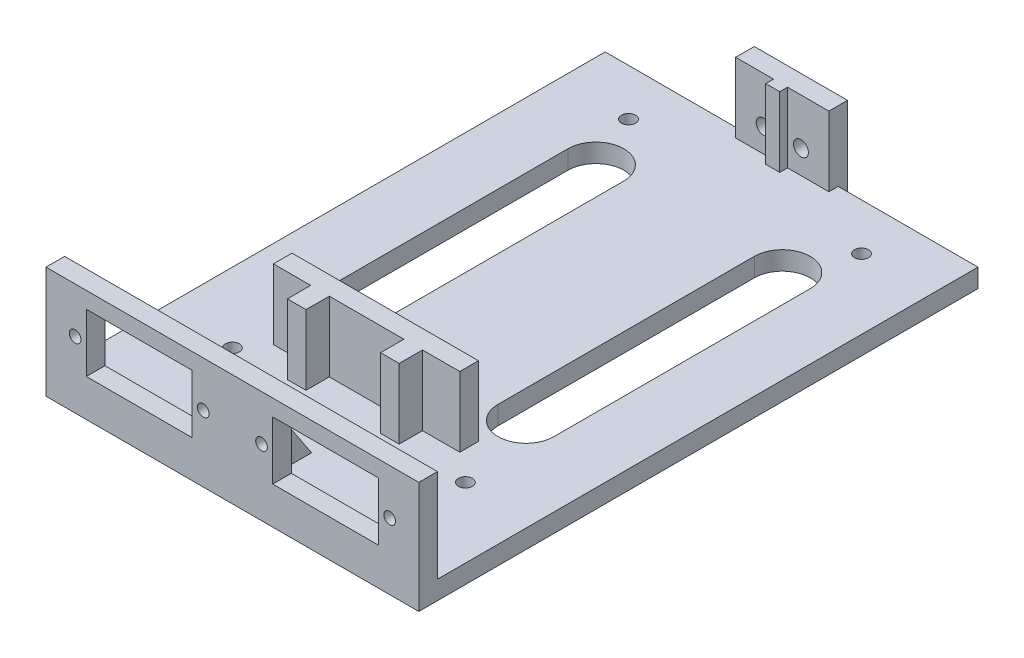
SolidWorks part; units mm, degrees
ref_plane "前视基准面" through (0, 0, 0) normal (0, 0, 1) x (1, 0, 0)
ref_plane "上视基准面" through (0, 0, 0) normal (0, 1, 0) x (1, 0, 0)
ref_plane "右视基准面" through (0, 0, 0) normal (1, 0, 0) x (0, 0, -1)
other "Configuration Table"
sketch "草图1" plane through (0, 0, 0) normal (0, 1, 0) x (1, 0, 0)
  line L0 (1.1114, 177.4615) -> (1.1114, -116.9271) construction
  line L1 (-38.8886, 30.2672) -> (41.1114, 30.2672)
  line L2 (-38.8886, 30.2672) -> (-38.8886, -89.7328)
  line L3 (-38.8886, -89.7328) -> (41.1114, -89.7328)
  line L4 (41.1114, 30.2672) -> (41.1114, -89.7328)
  circle A0 centre (-23.8886, 20.2672) radius 1.5
  circle A1 centre (26.1114, 20.2672) radius 1.5
  circle A2 centre (-23.8886, -64.7328) radius 1.5
  circle A3 centre (26.1114, -64.7328) radius 1.5
  point P4 (1.1114, -22.2328)
  point P15 (0, 0)
  point P16 (0, 61.7407)
  point P17 (0, 177.4615)
  point P26 (1.1114, 30.2672)
  dimension "D1" = 50
  dimension "D2" = 3
  dimension "D3" = 50
  dimension "D4" = 50
  dimension "D5" = 85
  dimension "D6" = 120
  dimension "D7" = 80
  dimension "D8" = 10
extrude "凸台-拉伸2" add sketch "草图1" along normal blind 4
sketch "草图4" plane through (0, 4, 0) normal (0, 1, 0) x (1, 0, 0)
  line L0 (41.1114, -89.7328) -> (41.1114, 30.2672) construction
  line L1 (-38.8886, -89.7328) -> (41.1114, -89.7328)
  line L2 (-38.8886, -89.7328) -> (-38.8886, -85.7328)
  line L3 (-38.8886, -85.7328) -> (41.1114, -85.7328)
  line L4 (41.1114, -89.7328) -> (41.1114, -85.7328)
  line L5 (-38.8886, -89.7328) -> (41.1114, -85.7328) construction
  line L6 (-38.8886, -85.7328) -> (41.1114, -89.7328) construction
  line L7 (41.1114, 30.2672) -> (-38.8886, 30.2672) construction
  line L8 (-8.8886, 32.2672) -> (11.1114, 32.2672)
  line L9 (-8.8886, 32.2672) -> (-8.8886, 28.2672)
  line L10 (-8.8886, 28.2672) -> (11.1114, 28.2672)
  line L11 (11.1114, 32.2672) -> (11.1114, 28.2672)
  line L12 (-8.8886, 32.2672) -> (11.1114, 28.2672) construction
  line L13 (-8.8886, 28.2672) -> (11.1114, 32.2672) construction
  line L14 (-38.8886, 30.2672) -> (-38.8886, -89.7328) construction
  line L15 (-23.8886, -75.7328) -> (-19.8886, -75.7328)
  line L16 (-23.8886, -75.7328) -> (-23.8886, -85.7328)
  line L17 (-23.8886, -85.7328) -> (-19.8886, -85.7328)
  line L18 (-19.8886, -75.7328) -> (-19.8886, -85.7328)
  line L19 (-23.8886, -75.7328) -> (-19.8886, -85.7328) construction
  line L20 (-23.8886, -85.7328) -> (-19.8886, -75.7328) construction
  line L21 (26.1114, -75.7328) -> (22.1114, -75.7328)
  line L22 (26.1114, -75.7328) -> (26.1114, -85.7328)
  line L23 (26.1114, -85.7328) -> (22.1114, -85.7328)
  line L24 (22.1114, -75.7328) -> (22.1114, -85.7328)
  line L25 (26.1114, -75.7328) -> (22.1114, -85.7328) construction
  line L26 (26.1114, -85.7328) -> (22.1114, -75.7328) construction
  point P4 (1.1114, -87.7328)
  point P8 (1.1114, 30.2672)
  point P19 (-21.8886, -80.7328)
  point P24 (24.1114, -80.7328)
  line M11 (-38.8886, 30.2672) -> (-38.8886, -89.7328)
  line M12 (-38.8886, -89.7328) -> (41.1114, -89.7328)
  line M13 (41.1114, -89.7328) -> (41.1114, 30.2672)
  dimension "D1" = 4
  dimension "D2" = 20
  dimension "D3" = 4
  dimension "D4" = 4
  dimension "D5" = 10
  dimension "D6" = 4
  dimension "D7" = 10
  dimension "D8" = 15
  dimension "D9" = 15
extrude "凸台-拉伸4" add sketch "草图4" along normal blind 20 contours L3 M11 M12 M13 | L21 L24 L3 L22 | L18 L15 L16 L3
sketch "草图5" plane through (0, 4, 0) normal (0, 1, 0) x (1, 0, 0)
  line L0 (41.1114, 30.2672) -> (-38.8886, 30.2672) construction
  line L1 (-8.8886, 32.2672) -> (11.1114, 32.2672)
  line L2 (-8.8886, 32.2672) -> (-8.8886, 28.2672)
  line L3 (-8.8886, 28.2672) -> (11.1114, 28.2672)
  line L4 (11.1114, 32.2672) -> (11.1114, 28.2672)
  line L5 (-8.8886, 32.2672) -> (11.1114, 28.2672) construction
  line L6 (-8.8886, 28.2672) -> (11.1114, 32.2672) construction
  point P0 (1.1114, 30.2672)
  dimension "D1" = 4
  dimension "D2" = 20
extrude "凸台-拉伸5" add sketch "草图5" along normal blind 15 and the other way blind 10
sketch "草图6" plane through (0, 0, -32.2672) normal (0, 0, -1) x (-1, 0, 0)
  line L0 (-1.1114, 20.4729) -> (-1.1114, -8.4859) construction
  circle A0 centre (2.8886, 9.0967) radius 1.6
  circle A1 centre (-5.1114, 9.0967) radius 1.6
  point P6 (0, 0)
  point P7 (0, 0)
  dimension "D1" = 8
  dimension "D2" = 3.2
  dimension "D3" = 8
extrude "切除-拉伸1" cut sketch "草图6" against normal up to next
sketch "草图9" plane through (-23.8886, 0, 0) normal (-1, 0, 0) x (0, 0, 1)
  line L0 (75.7328, 4) -> (85.7328, 14)
  line L1 (85.7328, 14) -> (85.7328, 24)
  line L2 (75.7328, 24) -> (75.7328, 4)
  line L4 (75.7328, 4) -> (85.7328, 4)
  line L5 (85.7328, 4) -> (85.7328, 24)
  line L6 (85.7328, 24) -> (75.7328, 24)
  line L7 (75.7328, 24) -> (75.7328, 4)
  line L8 (75.7328, 4) -> (85.7328, 4)
  line L9 (85.7328, 4) -> (85.7328, 24)
  line L10 (85.7328, 24) -> (75.7328, 24)
  line L11 (75.7328, 24) -> (75.7328, 4)
  dimension "D1" = 0
extrude "切除-拉伸3" cut sketch "草图9" against normal up to next contours L0 L1
sketch "草图10" plane through (0, 4, 0) normal (0, 1, 0) x (1, 0, 0)
  line L1 (-0.7696, 29.5947) -> (2.2304, 29.5947)
  line L2 (-0.7696, 29.5947) -> (-0.7696, 26.5947)
  line L3 (-0.7696, 26.5947) -> (2.2304, 26.5947)
  line L4 (2.2304, 29.5947) -> (2.2304, 26.5947)
  line L5 (-0.7696, 29.5947) -> (2.2304, 26.5947) construction
  line L6 (-0.7696, 26.5947) -> (2.2304, 29.5947) construction
  line L16 (41.1114, -85.7328) -> (41.1114, 30.2672)
  line L17 (41.1114, 30.2672) -> (11.1114, 30.2672)
  line L18 (11.1114, 30.2672) -> (11.1114, 28.2672)
  line L19 (11.1114, 28.2672) -> (-8.8886, 28.2672)
  line L20 (-8.8886, 28.2672) -> (-8.8886, 30.2672)
  line L21 (-8.8886, 30.2672) -> (-38.8886, 30.2672)
  line L22 (-38.8886, 30.2672) -> (-38.8886, -85.7328)
  line L23 (-38.8886, -85.7328) -> (-23.8886, -85.7328)
  line L24 (-23.8886, -85.7328) -> (-23.8886, -75.7328)
  line L25 (-23.8886, -75.7328) -> (-19.8886, -75.7328)
  line L26 (-19.8886, -75.7328) -> (-19.8886, -85.7328)
  line L27 (-19.8886, -85.7328) -> (22.1114, -85.7328)
  line L28 (22.1114, -85.7328) -> (22.1114, -75.7328)
  line L29 (22.1114, -75.7328) -> (26.1114, -75.7328)
  line L30 (26.1114, -75.7328) -> (26.1114, -85.7328)
  line L31 (26.1114, -85.7328) -> (41.1114, -85.7328)
  line L32 (41.1114, -85.7328) -> (41.1114, 30.2672)
  line L33 (41.1114, 30.2672) -> (11.1114, 30.2672)
  line L34 (11.1114, 30.2672) -> (11.1114, 28.2672)
  line L35 (11.1114, 28.2672) -> (-8.8886, 28.2672)
  line L36 (-8.8886, 28.2672) -> (-8.8886, 30.2672)
  line L37 (-8.8886, 30.2672) -> (-38.8886, 30.2672)
  line L38 (-38.8886, 30.2672) -> (-38.8886, -85.7328)
  line L39 (-38.8886, -85.7328) -> (-23.8886, -85.7328)
  line L40 (-23.8886, -85.7328) -> (-23.8886, -75.7328)
  line L41 (-23.8886, -75.7328) -> (-19.8886, -75.7328)
  line L42 (-19.8886, -75.7328) -> (-19.8886, -85.7328)
  line L43 (-19.8886, -85.7328) -> (22.1114, -85.7328)
  line L44 (22.1114, -85.7328) -> (22.1114, -75.7328)
  line L45 (22.1114, -75.7328) -> (26.1114, -75.7328)
  line L46 (26.1114, -75.7328) -> (26.1114, -85.7328)
  line L47 (26.1114, -85.7328) -> (41.1114, -85.7328)
  point P2 (0.7304, 28.0947)
  dimension "D2" = 3
  dimension "D3" = 3
  dimension "D1" = 0
extrude "凸台-拉伸7" add sketch "草图10" along normal blind 15 and the other way blind 10 contours L2 L1 L4 L3
sketch "草图11" plane through (0, 4, 0) normal (0, 1, 0) x (1, 0, 0)
  line L0 (-0.0942, -99.8819) -> (-0.0942, 37.9909) construction
  line L1 (-38.8886, -89.7328) -> (41.1114, -89.7328) construction
  line L2 (-20.0942, -55.7328) -> (19.9058, -55.7328)
  line L3 (-20.0942, -55.7328) -> (-20.0942, -59.7328)
  line L4 (-20.0942, -59.7328) -> (19.9058, -59.7328)
  line L5 (19.9058, -55.7328) -> (19.9058, -59.7328)
  line L6 (-20.0942, -55.7328) -> (19.9058, -59.7328) construction
  line L7 (-20.0942, -59.7328) -> (19.9058, -55.7328) construction
  line L9 (7.9058, -59.7328) -> (11.9058, -59.7328)
  line L10 (7.9058, -59.7328) -> (7.9058, -64.7328)
  line L11 (7.9058, -64.7328) -> (11.9058, -64.7328)
  line L12 (11.9058, -59.7328) -> (11.9058, -64.7328)
  line L13 (7.9058, -59.7328) -> (11.9058, -64.7328) construction
  line L14 (7.9058, -64.7328) -> (11.9058, -59.7328) construction
  line L15 (-12.4221, -59.7328) -> (-9.203, -59.7328)
  line L16 (-8.0942, -64.7328) -> (-12.0942, -64.7328)
  line L17 (-8.0942, -64.7328) -> (-8.0942, -59.7328)
  line L18 (-8.0942, -59.7328) -> (-12.0942, -59.7328)
  line L19 (-12.0942, -64.7328) -> (-12.0942, -59.7328)
  line L20 (-8.0942, -64.7328) -> (-12.0942, -59.7328) construction
  line L21 (-8.0942, -59.7328) -> (-12.0942, -64.7328) construction
  point P2 (-0.0942, -57.7328)
  point P13 (9.9058, -62.2328)
  point P20 (-10.0942, -62.2328)
  dimension "D1" = 4
  dimension "D2" = 40
  dimension "D3" = 30
  dimension "D4" = 4
  dimension "D5" = 5
  dimension "D6" = 10
  dimension "D7" = 4
  dimension "D8" = 5
  dimension "D9" = 10
extrude "凸台-拉伸9" add sketch "草图11" along normal blind 15 contours L5 L2 L3 L4 L15 | L19 L16 L17 L4 L15 | L12 L4 L10 L11
sketch "草图12" plane through (0, 4, 0) normal (0, 1, 0) x (1, 0, 0)
  line L0 (1.1114, -104.8099) -> (1.1114, 64.1147) construction
  line L1 (21.1114, 8.2672) -> (21.1114, -46.7328) construction
  line L2 (27.1114, 8.2672) -> (27.1114, -46.7328)
  line L3 (15.1114, 8.2672) -> (15.1114, -46.7328)
  line L4 (-18.8886, 8.2672) -> (-18.8886, -46.7328) construction
  line L5 (-12.8886, 8.2672) -> (-12.8886, -46.7328)
  line L6 (-24.8886, 8.2672) -> (-24.8886, -46.7328)
  line L20 (-0.7696, 26.5947) -> (-0.7696, 28.2672)
  line L21 (-0.7696, 28.2672) -> (-8.8886, 28.2672)
  line L22 (-8.8886, 28.2672) -> (-8.8886, 30.2672)
  line L23 (-8.8886, 30.2672) -> (-38.8886, 30.2672)
  line L24 (-38.8886, 30.2672) -> (-38.8886, -85.7328)
  line L25 (-38.8886, -85.7328) -> (-23.8886, -85.7328)
  line L26 (-23.8886, -85.7328) -> (-23.8886, -75.7328)
  line L27 (-23.8886, -75.7328) -> (-19.8886, -75.7328)
  line L28 (-19.8886, -75.7328) -> (-19.8886, -85.7328)
  line L29 (-19.8886, -85.7328) -> (22.1114, -85.7328)
  line L30 (22.1114, -85.7328) -> (22.1114, -75.7328)
  line L31 (22.1114, -75.7328) -> (26.1114, -75.7328)
  line L32 (26.1114, -75.7328) -> (26.1114, -85.7328)
  line L33 (26.1114, -85.7328) -> (41.1114, -85.7328)
  line L34 (41.1114, -85.7328) -> (41.1114, 30.2672)
  line L35 (41.1114, 30.2672) -> (11.1114, 30.2672)
  line L36 (11.1114, 30.2672) -> (11.1114, 28.2672)
  line L37 (11.1114, 28.2672) -> (2.2304, 28.2672)
  line L38 (2.2304, 28.2672) -> (2.2304, 26.5947)
  line L39 (2.2304, 26.5947) -> (-0.7696, 26.5947)
  line L40 (-0.7696, 26.5947) -> (-0.7696, 28.2672)
  line L41 (-0.7696, 28.2672) -> (-8.8886, 28.2672)
  line L42 (-8.8886, 28.2672) -> (-8.8886, 30.2672)
  line L43 (-8.8886, 30.2672) -> (-38.8886, 30.2672)
  line L44 (-38.8886, 30.2672) -> (-38.8886, -85.7328)
  line L45 (-38.8886, -85.7328) -> (-23.8886, -85.7328)
  line L46 (-23.8886, -85.7328) -> (-23.8886, -75.7328)
  line L47 (-23.8886, -75.7328) -> (-19.8886, -75.7328)
  line L48 (-19.8886, -75.7328) -> (-19.8886, -85.7328)
  line L49 (-19.8886, -85.7328) -> (22.1114, -85.7328)
  line L50 (22.1114, -85.7328) -> (22.1114, -75.7328)
  line L51 (22.1114, -75.7328) -> (26.1114, -75.7328)
  line L52 (26.1114, -75.7328) -> (26.1114, -85.7328)
  line L53 (26.1114, -85.7328) -> (41.1114, -85.7328)
  line L54 (41.1114, -85.7328) -> (41.1114, 30.2672)
  line L55 (41.1114, 30.2672) -> (11.1114, 30.2672)
  line L56 (11.1114, 30.2672) -> (11.1114, 28.2672)
  line L57 (11.1114, 28.2672) -> (2.2304, 28.2672)
  line L58 (2.2304, 28.2672) -> (2.2304, 26.5947)
  line L59 (2.2304, 26.5947) -> (-0.7696, 26.5947)
  arc A0 (27.1114, 8.2672) -> (15.1114, 8.2672) centre (21.1114, 8.2672) ccw
  arc A1 (15.1114, -46.7328) -> (27.1114, -46.7328) centre (21.1114, -46.7328) ccw
  arc A2 (-12.8886, 8.2672) -> (-24.8886, 8.2672) centre (-18.8886, 8.2672) ccw
  arc A3 (-24.8886, -46.7328) -> (-12.8886, -46.7328) centre (-18.8886, -46.7328) ccw
  point P10 (21.1114, -19.2328)
  point P20 (-18.8886, -19.2328)
  point P34 (0, 0)
  point P36 (0, 0)
  point P38 (0, 0)
  point P39 (0, 0)
  point P40 (0, 0)
  point P41 (30.5874, -46.1774)
  point P42 (0, 0)
  point P43 (0, 0)
  dimension "D3" = 6
  dimension "D2" = 55
  dimension "D4" = 20
  dimension "D5" = 20
  dimension "D6" = 20
  dimension "D7" = 22
  dimension "D8" = 22
  dimension "D1" = 0
extrude "切除-拉伸5" cut sketch "草图12" against normal up to next contours L6 A2 L5 A3 | L3 A1 L2 A0
sketch "草图13" plane through (0, 0, 85.7328) normal (0, 0, -1) x (-1, 0, 0)
  line L0 (-1.1114, 33.188) -> (-1.1114, -2.1112) construction
  line L1 (-32.4614, 20.5) -> (-9.7614, 20.5)
  line L2 (-32.4614, 20.5) -> (-32.4614, 8)
  line L3 (-32.4614, 8) -> (-9.7614, 8)
  line L4 (-9.7614, 20.5) -> (-9.7614, 8)
  line L5 (-32.4614, 20.5) -> (-9.7614, 8) construction
  line L6 (-32.4614, 8) -> (-9.7614, 20.5) construction
  line L7 (-21.1114, 29.5176) -> (-21.1114, 2.8371) construction
  line L8 (18.8886, 29.5176) -> (18.8886, 2.8371) construction
  line L9 (30.2386, 8) -> (7.5386, 20.5) construction
  line L10 (30.2386, 20.5) -> (7.5386, 8) construction
  line L11 (19.8886, 14) -> (19.8886, 4)
  line L12 (23.8886, 4) -> (38.8886, 4)
  line L13 (38.8886, 4) -> (38.8886, 24)
  line L14 (38.8886, 24) -> (-41.1114, 24)
  line L15 (-41.1114, 24) -> (-41.1114, 4)
  line L16 (-41.1114, 4) -> (-26.1114, 4)
  line L17 (-26.1114, 4) -> (-26.1114, 14)
  line L18 (-26.1114, 14) -> (-22.1114, 14)
  line L19 (-22.1114, 14) -> (-22.1114, 4)
  line L20 (-22.1114, 4) -> (19.8886, 4)
  line L21 (19.8886, 4) -> (19.8886, 14)
  line L22 (19.8886, 14) -> (23.8886, 14)
  line L23 (23.8886, 14) -> (23.8886, 4)
  line L24 (23.8886, 4) -> (38.8886, 4)
  line L25 (38.8886, 4) -> (38.8886, 24)
  line L26 (38.8886, 24) -> (-41.1114, 24)
  line L27 (-41.1114, 24) -> (-41.1114, 4)
  line L28 (-41.1114, 4) -> (-26.1114, 4)
  line L29 (-26.1114, 4) -> (-26.1114, 14)
  line L30 (-26.1114, 14) -> (-22.1114, 14)
  line L31 (-22.1114, 14) -> (-22.1114, 4)
  line L32 (-22.1114, 4) -> (19.8886, 4)
  line L33 (19.8886, 4) -> (19.8886, 14)
  line L34 (19.8886, 14) -> (23.8886, 14)
  line L35 (23.8886, 14) -> (23.8886, 4)
  line L36 (23.8886, 14) -> (19.8886, 14)
  line L37 (23.8886, 4) -> (23.8886, 14)
  line L38 (38.8886, 24) -> (38.8886, 4)
  line L39 (7.5386, 20.5) -> (7.5386, 8)
  line L40 (30.2386, 8) -> (7.5386, 8)
  line L41 (30.2386, 20.5) -> (30.2386, 8)
  line L42 (30.2386, 20.5) -> (7.5386, 20.5)
  circle A0 centre (-34.8614, 14.25) radius 1.25
  circle A1 centre (-7.3614, 14.25) radius 1.25
  circle A2 centre (5.1386, 14.25) radius 1.25
  circle A3 centre (32.6386, 14.25) radius 1.25
  point P2 (-21.1114, 14.25)
  point P35 (18.8886, 14.25)
  dimension "D5" = 27.5
  dimension "D7" = 2.5
  dimension "D2" = 22.7
  dimension "D3" = 12.5
  dimension "D4" = 20
  dimension "D6" = 27.5
  dimension "D8" = 4
  dimension "D1" = 0
extrude "切除-拉伸6" cut sketch "草图13" against normal up to next contours A0 | L1 L4 L3 L2 | A1 | A2 | L42 L39 L40 L41 | A3
sketch "草图14" plane through (26.1114, 0, 0) normal (1, 0, 0) x (0, 0, -1)
  line L4 (-85.7328, 4) -> (-75.7328, 4)
  line L5 (-75.7328, 4) -> (-85.7328, 14)
  line L6 (-85.7328, 14) -> (-85.7328, 8)
  line L7 (-85.7328, 8) -> (-85.7328, 4)
  line L8 (-85.7328, 4) -> (-75.7328, 4)
  line L9 (-75.7328, 4) -> (-85.7328, 14)
  line L10 (-85.7328, 14) -> (-85.7328, 8)
  line L11 (-85.7328, 8) -> (-85.7328, 4)
  dimension "D1" = 0
extrude "切除-拉伸7" cut sketch "草图14" against normal through all
sketch "草图15" plane through (0, 4, 0) normal (0, 1, 0) x (1, 0, 0)
  line L1 (-1.8886, -95.7328) -> (4.1114, -95.7328)
  line L2 (-1.8886, -95.7328) -> (-1.8886, -75.7328)
  line L3 (-1.8886, -75.7328) -> (4.1114, -75.7328)
  line L4 (4.1114, -95.7328) -> (4.1114, -75.7328)
  line L5 (-1.8886, -95.7328) -> (4.1114, -75.7328) construction
  line L6 (-1.8886, -75.7328) -> (4.1114, -95.7328) construction
  line L12 (-38.8886, -85.7328) -> (41.1114, -85.7328)
  line L13 (41.1114, -85.7328) -> (41.1114, 30.2672)
  line L14 (41.1114, 30.2672) -> (11.1114, 30.2672)
  line L15 (11.1114, 30.2672) -> (11.1114, 28.2672)
  line L16 (11.1114, 28.2672) -> (2.2304, 28.2672)
  line L17 (2.2304, 28.2672) -> (2.2304, 26.5947)
  line L18 (2.2304, 26.5947) -> (-0.7696, 26.5947)
  line L19 (-0.7696, 26.5947) -> (-0.7696, 28.2672)
  line L20 (-0.7696, 28.2672) -> (-8.8886, 28.2672)
  line L21 (-8.8886, 28.2672) -> (-8.8886, 30.2672)
  line L22 (-8.8886, 30.2672) -> (-38.8886, 30.2672)
  line L23 (-38.8886, 30.2672) -> (-38.8886, -85.7328)
  line L24 (-38.8886, -85.7328) -> (41.1114, -85.7328)
  line L25 (41.1114, -85.7328) -> (41.1114, 30.2672)
  line L26 (41.1114, 30.2672) -> (11.1114, 30.2672)
  line L27 (11.1114, 30.2672) -> (11.1114, 28.2672)
  line L28 (11.1114, 28.2672) -> (2.2304, 28.2672)
  line L29 (2.2304, 28.2672) -> (2.2304, 26.5947)
  line L30 (2.2304, 26.5947) -> (-0.7696, 26.5947)
  line L31 (-0.7696, 26.5947) -> (-0.7696, 28.2672)
  line L32 (-0.7696, 28.2672) -> (-8.8886, 28.2672)
  line L33 (-8.8886, 28.2672) -> (-8.8886, 30.2672)
  line L34 (-8.8886, 30.2672) -> (-38.8886, 30.2672)
  line L35 (-38.8886, 30.2672) -> (-38.8886, -85.7328)
  point P2 (1.1114, -85.7328)
  point P12 (0, 0)
  point P16 (13.4045, -98.5907)
  line M17 (-38.8886, -85.7328) -> (41.1114, -85.7328)
  dimension "D2" = 6
  dimension "D3" = 20
  dimension "D1" = 0
extrude "凸台-拉伸10" add sketch "草图15" along normal blind 15 contours L4 L3 L2 M17
sketch "草图16" plane through (4.1114, 0, 0) normal (1, 0, 0) x (0, 0, -1)
  line L0 (-85.7328, 19) -> (-75.7328, 4)
  line L1 (-75.7328, 19) -> (-75.7328, 4) construction
  line L2 (-75.7328, 4) -> (-75.7328, 19)
  line L3 (-75.7328, 19) -> (-85.7328, 19)
extrude "切除-拉伸8" cut sketch "草图16" against normal up to next
sketch "草图17" plane through (0, 0, 0) normal (0, -1, 0) x (1, 0, 0)
  line L12 (-8.8886, -28.2672) -> (-0.7696, -28.2672)
  line L13 (-0.7696, -28.2672) -> (-0.7696, -26.5947)
  line L14 (-0.7696, -26.5947) -> (2.2304, -26.5947)
  line L15 (2.2304, -26.5947) -> (2.2304, -28.2672)
  line L16 (2.2304, -28.2672) -> (11.1114, -28.2672)
  line L17 (11.1114, -28.2672) -> (11.1114, -30.2672)
  line L18 (11.1114, -30.2672) -> (41.1114, -30.2672)
  line L19 (41.1114, -30.2672) -> (41.1114, 89.7328)
  line L20 (41.1114, 89.7328) -> (-38.8886, 89.7328)
  line L21 (-38.8886, 89.7328) -> (-38.8886, -30.2672)
  line L22 (-38.8886, -30.2672) -> (-8.8886, -30.2672)
  line L23 (-8.8886, -30.2672) -> (-8.8886, -28.2672)
  line L24 (-8.8886, -28.2672) -> (-0.7696, -28.2672)
  line L25 (-0.7696, -28.2672) -> (-0.7696, -26.5947)
  line L26 (-0.7696, -26.5947) -> (2.2304, -26.5947)
  line L27 (2.2304, -26.5947) -> (2.2304, -28.2672)
  line L28 (2.2304, -28.2672) -> (11.1114, -28.2672)
  line L29 (11.1114, -28.2672) -> (11.1114, -30.2672)
  line L30 (11.1114, -30.2672) -> (41.1114, -30.2672)
  line L31 (41.1114, -30.2672) -> (41.1114, 89.7328)
  line L32 (41.1114, 89.7328) -> (-38.8886, 89.7328)
  line L33 (-38.8886, 89.7328) -> (-38.8886, -30.2672)
  line L34 (-38.8886, -30.2672) -> (-8.8886, -30.2672)
  line L35 (-8.8886, -30.2672) -> (-8.8886, -28.2672)
  circle A0 centre (-23.8886, 64.7328) radius 3
  circle A1 centre (26.1114, 64.7328) radius 3
  circle A2 centre (26.1114, -20.2672) radius 3
  circle A3 centre (-23.8886, -20.2672) radius 3
  circle A6 centre (-23.8886, 64.7328) radius 1.5
  circle A7 centre (26.1114, 64.7328) radius 1.5
  circle A8 centre (26.1114, -20.2672) radius 1.5
  circle A9 centre (-23.8886, -20.2672) radius 1.5
  circle M37 centre (-23.8886, -20.2672) radius 1.5
  circle M38 centre (26.1114, -20.2672) radius 1.5
  circle M39 centre (-23.8886, 64.7328) radius 1.5
  circle M40 centre (26.1114, 64.7328) radius 1.5
  dimension "D1" = 6
  dimension "D2" = 0
extrude "凸台-拉伸11" add sketch "草图17" along normal blind 3 contours A0 M39 | A1 M40 | A2 M38 | A3 M37 | A7
equation "\"30、\"=35.8907"
